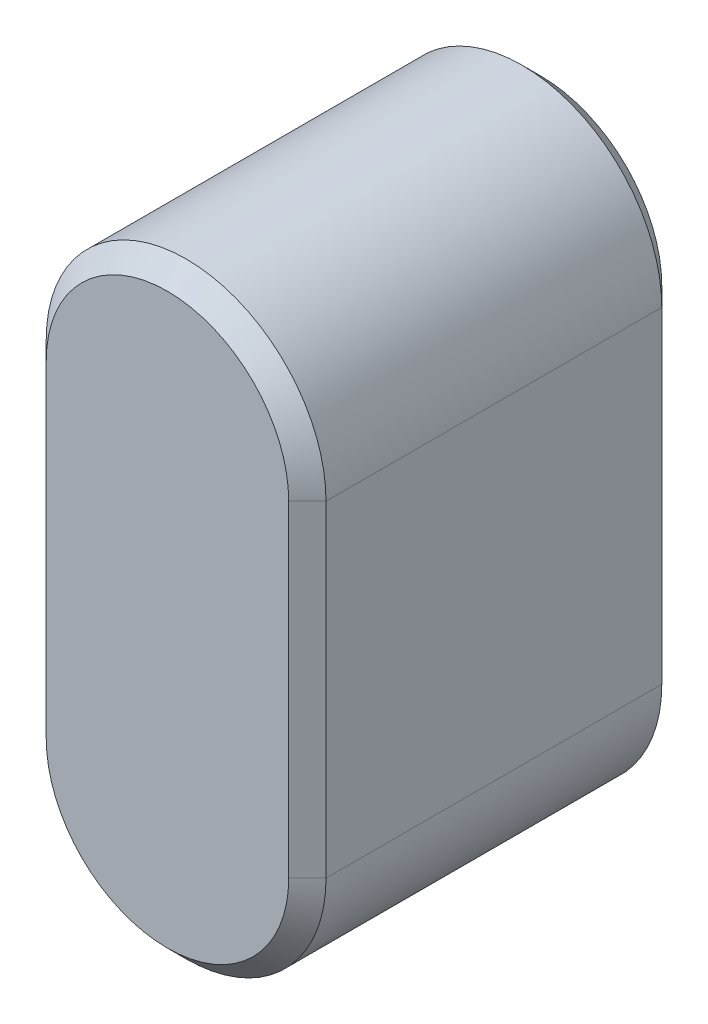
SolidWorks part; units mm, degrees
ref_plane "前视基准面" through (0, 0, 0) normal (0, 0, 1) x (1, 0, 0)
ref_plane "上视基准面" through (0, 0, 0) normal (0, 1, 0) x (1, 0, 0)
ref_plane "右视基准面" through (0, 0, 0) normal (1, 0, 0) x (0, 0, -1)
sketch "草图1" plane through (0, 0, 0) normal (0, 0, 1) x (1, 0, 0)
  line L0 (0, -1.75) -> (0, 1.75) construction
  line L1 (-1.5, -1.75) -> (-1.5, 1.75)
  line L2 (1.5, -1.75) -> (1.5, 1.75)
  arc A0 (-1.5, -1.75) -> (1.5, -1.75) centre (0, -1.75) ccw
  arc A1 (1.5, 1.75) -> (-1.5, 1.75) centre (0, 1.75) ccw
  point P2 (0, 0)
  dimension "D1" = 1.5
  dimension "D2" = 3.5
extrude "凸台-拉伸1" add sketch "草图1" along normal blind 4
chamfer "倒角1" distance 0.2 angle 45 8 edges at (-1.5, 0, 0) (0, 3.25, 0) (1.5, 0, 0) (0, -3.25, 0) (0, -3.25, 4) (1.5, 0, 4) (-1.5, 0, 4) (0, 3.25, 4)
